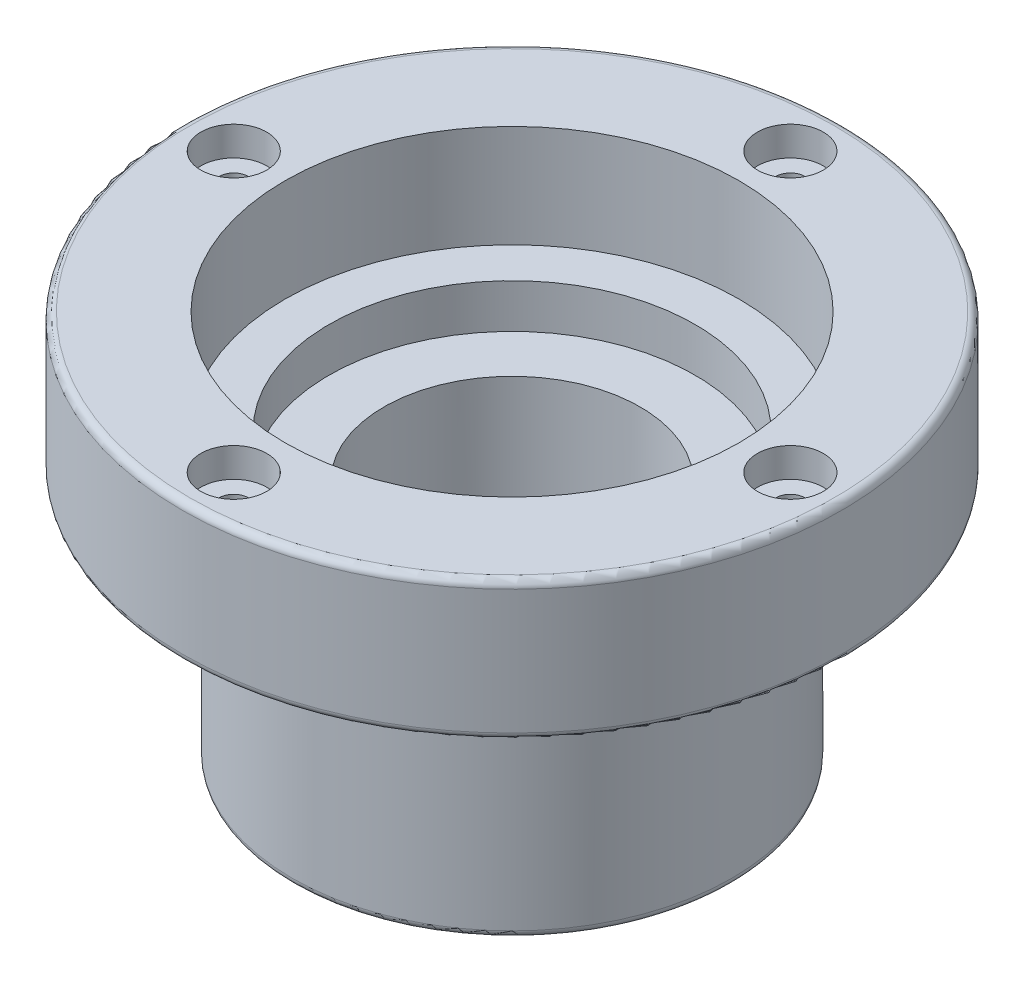
SolidWorks part; units mm, degrees
material "1060 合金"
ref_plane "前视基准面" through (0, 0, 0) normal (0, 0, 1) x (1, 0, 0)
ref_plane "上视基准面" through (0, 0, 0) normal (0, 1, 0) x (1, 0, 0)
ref_plane "右视基准面" through (0, 0, 0) normal (1, 0, 0) x (0, 0, -1)
sketch "草图1" plane through (0, 0, 0) normal (0, 1, 0) x (1, 0, 0)
  circle A0 centre (0, 0) radius 45
extrude "凸台-拉伸2" add sketch "草图1" against normal blind 19
sketch "草图3" plane through (0, -19, 0) normal (0, -1, 0) x (1, 0, 0)
  circle A0 centre (0, 0) radius 30
extrude "凸台-拉伸3" add sketch "草图3" along normal blind 34
sketch "草图8" plane through (0, -53, 0) normal (0, -1, 0) x (1, 0, 0)
  circle A0 centre (0, 0) radius 23.5
extrude "切除-拉伸2" cut sketch "草图8" against normal blind 14
sketch "草图9" plane through (0, 0, 0) normal (0, 1, 0) x (1, 0, 0)
  circle A0 centre (0, 0) radius 31
extrude "切除-拉伸4" cut sketch "草图9" against normal blind 14
sketch "草图11" plane through (0, -14, 0) normal (0, 1, 0) x (1, 0, 0)
  circle A0 centre (0, 0) radius 25
extrude "切除-拉伸6" cut sketch "草图11" against normal blind 6
sketch "草图12" plane through (0, -20, 0) normal (0, 1, 0) x (1, 0, 0)
  circle A0 centre (0, 0) radius 17.5
extrude "切除-拉伸7" cut sketch "草图12" against normal blind 60
sketch "草图14" plane through (0, 0, 0) normal (0, 1, 0) x (1, 0, 0)
  circle A0 centre (0, 38) radius 2
  point P0 (0, 0)
extrude "切除-拉伸8" cut sketch "草图14" against normal blind 20
pattern_circular "阵列(圆周)1" count 4 over 360 about axis through (0, 0, 0) along (0, 1, 0) of "切除-拉伸8"
sketch "草图15" plane through (0, -53, 0) normal (0, -1, 0) x (1, 0, 0)
  circle A0 centre (0, 27) radius 1.5
extrude "切除-拉伸9" cut sketch "草图15" against normal blind 12
pattern_circular "阵列(圆周)2" count 4 over 360 about axis through (0, 0, 0) along (0, 1, 0) of "切除-拉伸9"
fillet "圆角1" radius 1 4 edges at (0, -53, -30) (0, -19, -30) (0, -19, 45) (0, 0, 45)
sketch "草图16" plane through (0, 0, 0) normal (0, 1, 0) x (1, 0, 0)
  circle A0 centre (-38, 0) radius 4.5
extrude "切除-拉伸10" cut sketch "草图16" against normal blind 4
pattern_circular "阵列(圆周)3" count 4 over 360 about axis through (0, 0, 0) along (0, 1, 0) of "切除-拉伸10"
